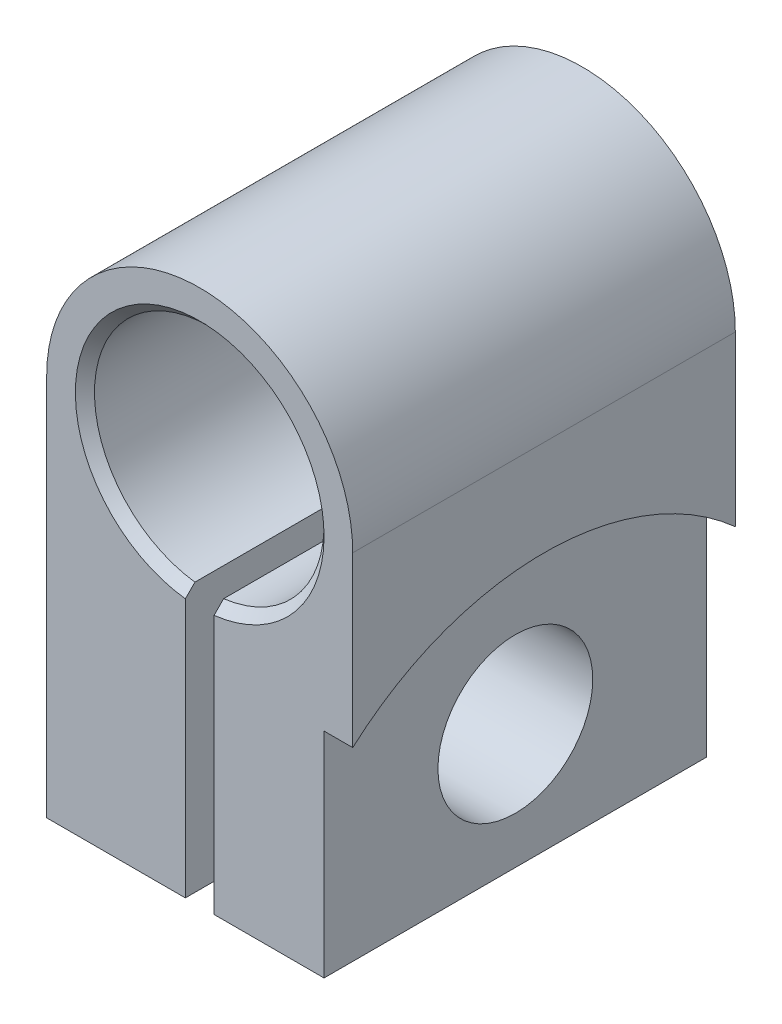
SolidWorks part; units mm, degrees
ref_plane "Piano frontale" through (0, 0, 0) normal (0, 0, 1) x (1, 0, 0)
ref_plane "Piano superiore" through (0, 0, 0) normal (0, 1, 0) x (1, 0, 0)
ref_plane "Piano destro" through (0, 0, 0) normal (1, 0, 0) x (0, 0, -1)
sketch "Schizzo2" plane through (0, 0, 0) normal (0, 0, 1) x (1, 0, 0)
  line L0 (0, 23.6157) -> (0, -23.6157) construction
  line L1 (8, -13.9837) -> (-8, -13.9837)
  line L2 (-8, -13.9837) -> (-8, 6.0163)
  line L3 (8, -13.9837) -> (8, 6.0163)
  arc A0 (-8, 6.0163) -> (8, 6.0163) centre (0, 6.0163) cw
  point P4 (0, 0)
  point P8 (0, 14.0163)
  point P10 (0, -13.9837)
  dimension "D4" = 6.0163
  dimension "D1" = 16
  dimension "D2" = 20
  dimension "D3" = 8
extrude "Estrusione-Estrusione1" add sketch "Schizzo2" against normal blind 20
sketch "Schizzo3" plane through (0, 0, 0) normal (0, 0, 1) x (1, 0, 0)
  line L0 (-8, -13.9837) -> (8, -13.9837) construction
  circle A0 centre (0, 6.0163) radius 6
  dimension "D1" = 20
extrude "Taglio-Estrusione1" cut sketch "Schizzo3" against normal through all
sketch "Schizzo4" plane through (0, 0, 0) normal (0, 0, 1) x (1, 0, 0)
  line L0 (0, -13.9837) -> (0, 14.0163) construction
  line L1 (-8, -13.9837) -> (8, -13.9837) construction
  line L2 (0.75, -13.9837) -> (-0.75, -13.9837)
  line L3 (-0.75, -13.9837) -> (-0.75, 0.0634)
  line L4 (-0.75, 0.0634) -> (0.75, 0.0634)
  line L5 (0.75, -13.9837) -> (0.75, 0.0634)
  arc A0 (8, 6.0163) -> (-8, 6.0163) centre (0, 6.0163) ccw construction
  circle A1 centre (0, 6.0163) radius 6 construction
  point P14 (0, 0.0634)
  dimension "D1" = 1.5
extrude "Taglio-Estrusione2" cut sketch "Schizzo4" against normal through all
sketch "Schizzo5" plane through (8, 0, 0) normal (1, 0, 0) x (0, 0, -1)
  line L0 (20, -13.9837) -> (0, -13.9837) construction
  line L1 (20, 6.0163) -> (0, 6.0163) construction
  line L2 (10, -13.9837) -> (10, 6.0163) construction
  line L3 (0, -13.9837) -> (0, 6.0163) construction
  circle A0 centre (10, -13.9837) radius 15
  dimension "D1" = 10
extrude "Taglio-Estrusione3" cut sketch "Schizzo5" against normal blind 1.5 contours A0
sketch "Schizzo6" plane through (6.5, 0, 0) normal (1, 0, 0) x (0, 0, -1)
  line L0 (0, -2.8033) -> (0, -13.9837) construction
  line L1 (20, -13.9837) -> (0, -13.9837) construction
  circle A0 centre (10, -7.4837) radius 4.0466
  dimension "D1" = 10
  dimension "D2" = 6.5
extrude "Taglio-Estrusione4" cut sketch "Schizzo6" against normal up to next contours A0
chamfer "Smusso2" distance 0.5 angle 45 1 edges at (0, 12.0163, 0)
chamfer "Smusso3" distance 0.5 angle 45 1 edges at (0, 12.0163, -20)
